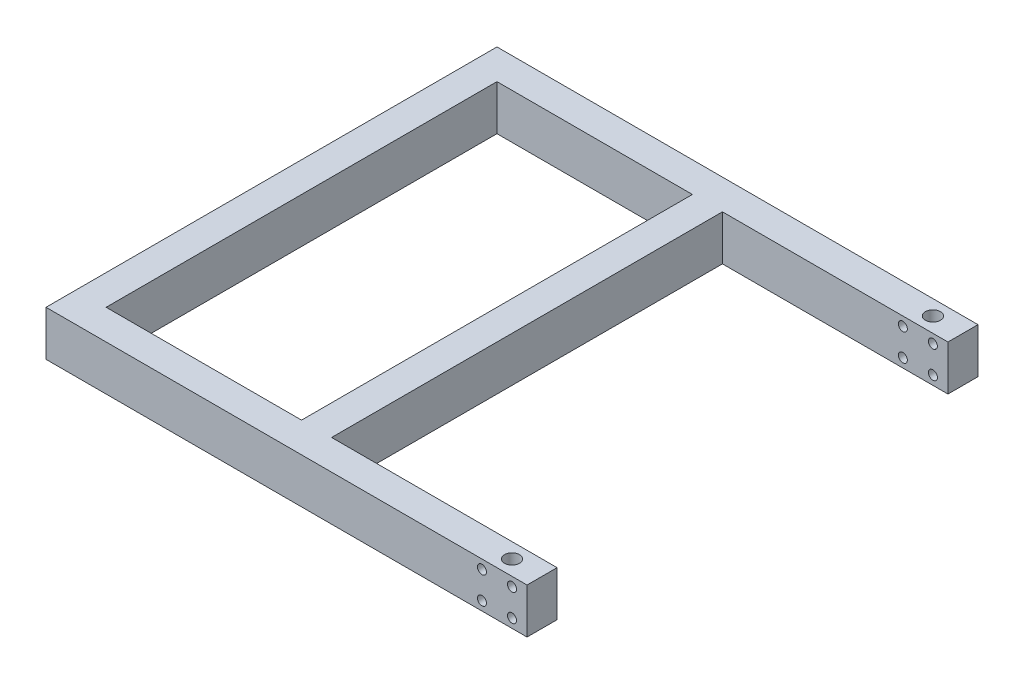
SolidWorks part; units mm, degrees
ref_plane "前视基准面" through (0, 0, 0) normal (0, 0, 1) x (1, 0, 0)
ref_plane "上视基准面" through (0, 0, 0) normal (0, 1, 0) x (1, 0, 0)
ref_plane "右视基准面" through (0, 0, 0) normal (1, 0, 0) x (0, 0, -1)
sketch "草图2" plane through (0, 0, 0) normal (0, 1, 0) x (1, 0, 0)
  line L0 (-160, 63.0645) -> (-160, -76.9355)
  line L1 (-160, -76.9355) -> (0, -76.9355)
  line L2 (0, -76.9355) -> (0, -66.9355)
  line L3 (0, -66.9355) -> (-75, -66.9355)
  line L4 (-75, -66.9355) -> (-75, 63.0645)
  line L5 (-75, 63.0645) -> (0, 63.0645)
  line L6 (0, 63.0645) -> (0, 73.0645)
  line L7 (0, 73.0645) -> (-160, 73.0645)
  line L8 (-160, 73.0645) -> (-160, 63.0645)
  line L9 (-85, 73.0645) -> (-85, -76.9355)
  line L10 (-75, 63.0645) -> (-160, 63.0645)
  line L11 (-75, -66.9355) -> (-160, -66.9355)
  line L12 (-150, 63.0645) -> (-150, -66.9355)
  dimension "D1" = 150
  dimension "D2" = 160
  dimension "D3" = 75
  dimension "1" = 85
  dimension "D4" = 10
  dimension "D5" = 10
  dimension "D6" = 10
extrude "凸台-拉伸1" add sketch "草图2" along normal blind 15 contours L10 L5 L6 L7 L9 | L10 L9 L7 L8 | L11 L4 L10 L9 | L3 L11 L9 L1 L2 | L9 L11 L0 L1 | L12 L10 L0 L11
sketch "草图3" plane through (0, 0, 76.9355) normal (0, 0, 1) x (1, 0, 0)
  line L0 (0, 15) -> (0, 0) construction
  line L1 (-160, 15) -> (0, 15) construction
  circle A0 centre (-5, 12) radius 1.5
  circle A1 centre (-5, 3) radius 1.5
  circle A2 centre (-15, 12) radius 1.5
  circle A3 centre (-15, 3) radius 1.5
  dimension "D1" = 3
  dimension "D2" = 3
  dimension "D3" = 3
  dimension "D4" = 3
  dimension "D5" = 5
  dimension "D6" = 5
  dimension "D7" = 10
  dimension "D8" = 10
  dimension "D9" = 3
  dimension "D10" = 3
  dimension "D11" = 9
extrude "切除-拉伸1" cut sketch "草图3" against normal through all
sketch "草图4" plane through (-160, 0, 0) normal (-1, 0, 0) x (0, 0, 1)
  line L0 (-73.0645, 15) -> (-73.0645, 0) construction
  line L1 (-73.0645, 15) -> (76.9355, 15) construction
  circle A0 centre (-63.0645, 7.5) radius 2.5
  circle A1 centre (-13.0645, 7.5) radius 2.5
  circle A2 centre (16.9355, 7.5) radius 2.5
  circle A3 centre (66.9355, 7.5) radius 2.5
  dimension "D1" = 5
  dimension "D2" = 5
  dimension "D3" = 5
  dimension "D4" = 5
  dimension "D8" = 50
  dimension "D5" = 10
  dimension "D6" = 50
  dimension "D7" = 30
  dimension "D9" = 7.5
extrude "切除-拉伸2" cut sketch "草图4" against normal blind 7 contours A0 | A1 | A2 | A3
sketch "草图5" plane through (0, 15, 0) normal (0, 1, 0) x (1, 0, 0)
  line L0 (0, 73.0645) -> (-160, 73.0645) construction
  line L1 (0, -66.9355) -> (-75, -66.9355) construction
  line L3 (0, 63.0645) -> (0, 73.0645) construction
  line L4 (0, -76.9355) -> (0, -66.9355) construction
  circle A0 centre (-10, 68.0645) radius 2.5
  circle A1 centre (-10, -71.9355) radius 2.5
  dimension "D1" = 5
  dimension "D2" = 5
  dimension "D3" = 5
  dimension "D4" = 5
  dimension "D5" = 10
  dimension "D6" = 10
extrude "切除-拉伸3" cut sketch "草图5" against normal through all
